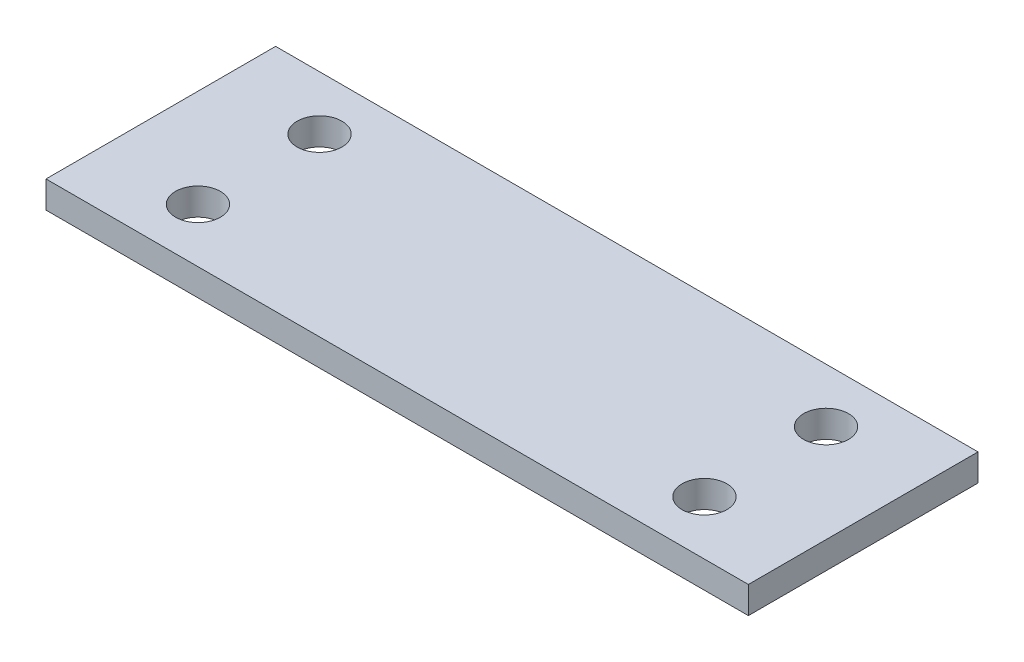
SolidWorks part; units mm, degrees
material "Silicon"
ref_plane "Front Plane" through (0, 0, 0) normal (0, 0, 1) x (1, 0, 0)
ref_plane "Top Plane" through (0, 0, 0) normal (0, 1, 0) x (1, 0, 0)
ref_plane "Right Plane" through (0, 0, 0) normal (1, 0, 0) x (0, 0, -1)
sketch "Sketch1" plane through (0, 0, 0) normal (0, 1, 0) x (1, 0, 0)
  line L1 (-61.664, 29.8532) -> (70.416, 29.8532)
  line L2 (-61.664, 29.8532) -> (-61.664, -13.3268)
  line L3 (-61.664, -13.3268) -> (70.416, -13.3268)
  line L4 (70.416, 29.8532) -> (70.416, -13.3268)
  dimension "D1" = 132.08
  dimension "D2" = 43.18
extrude "Boss-Extrude1" add sketch "Sketch1" along normal blind 5.08
sketch "Sketch2" plane through (0, 5.08, 0) normal (0, 1, 0) x (1, 0, 0)
  line L0 (-61.664, -13.3268) -> (70.416, -13.3268) construction
  line L1 (-61.664, 29.8532) -> (-61.664, -13.3268) construction
  line L2 (70.416, -13.3268) -> (70.416, 29.8532) construction
  point P0 (-43.249, 19.6932)
  point P1 (-43.249, -3.1668)
  point P2 (52.001, -3.1668)
  point P3 (52.001, 19.6932)
  dimension "D1" = 22.86
  dimension "D2" = 22.86
  dimension "D3" = 95.25
  dimension "D4" = 10.16
  dimension "D5" = 18.415
  dimension "D6" = 18.415
  dimension "D7" = 18.415
  dimension "D8" = 18.415
hole_wizard "13/64 (0.332) Diameter Hole1" positions "Sketch3" profile "Sketch5" hole size "13/64" standard "ANSI Inch" end condition through all
sketch "Sketch3" plane through (0, 5.08, 0) normal (0, 1, 0) x (1, 0, 0)
  point P0 (-43.249, 19.6932)
  point P4 (-43.249, -3.1668)
  point P7 (52.001, 19.6932)
  point P10 (52.001, -3.1668)
sketch "Sketch5" plane through (-43.249, 5.08, -19.6932) normal (1, 0, 0) x (0, 0, 1)
  line L0 (0, 0) -> (0, 5.08)
  line L1 (0, 5.08) -> (4.2164, 5.08)
  line L2 (4.2164, 5.08) -> (4.2164, 0)
  line L5 (4.2164, 0) -> (0, 0)
  line L11 (0, -6.35) -> (0, 107.95) construction
  dimension "Thru Hole Dia." = 8.4328
  dimension "Thru Hole Depth" = 5.08
